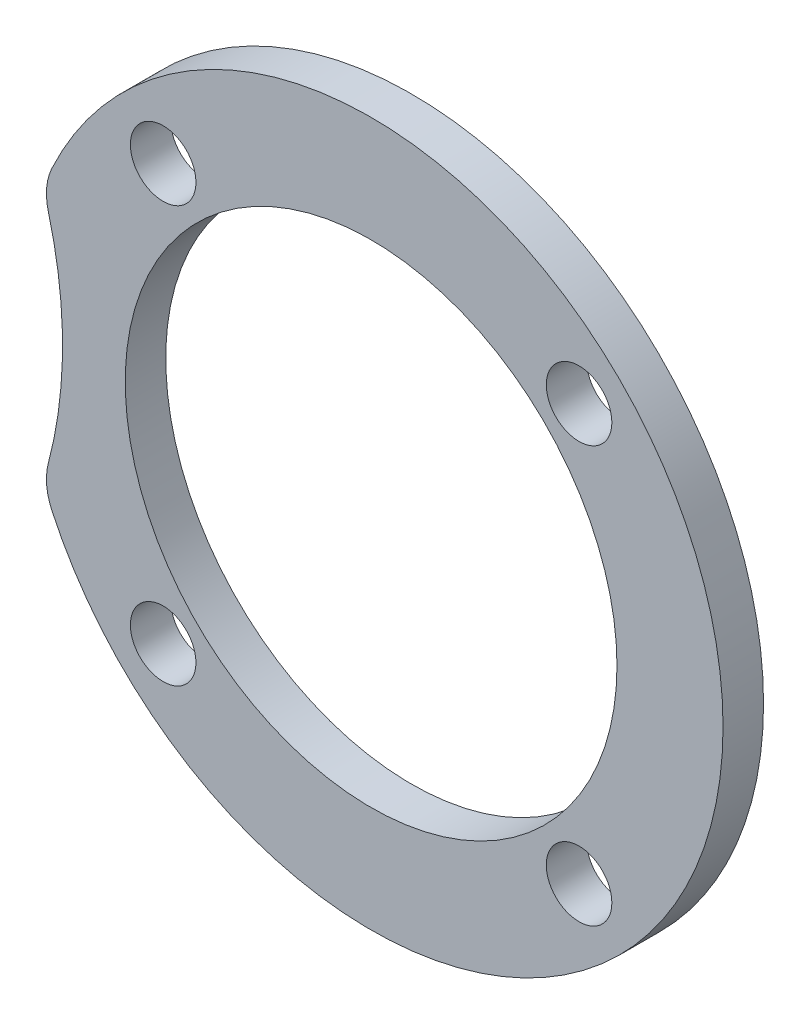
SolidWorks part; units mm, degrees
material "ABS"
ref_plane "前视基准面" through (0, 0, 0) normal (0, 0, 1) x (1, 0, 0)
ref_plane "上视基准面" through (0, 0, 0) normal (0, 1, 0) x (1, 0, 0)
ref_plane "右视基准面" through (0, 0, 0) normal (1, 0, 0) x (0, 0, -1)
sketch "草图1" plane through (0, 0, 0) normal (0, 0, 1) x (1, 0, 0)
  circle A0 centre (0, 0) radius 12.75
  circle A1 centre (0, 0) radius 18.25
  dimension "D1" = 25.5
  dimension "D2" = 36.5
extrude "凸台-拉伸1" add sketch "草图1" along normal mid plane 2.1
sketch "草图2" plane through (0, 0, 1.05) normal (0, 0, 1) x (1, 0, 0)
  line L0 (-38, 0) -> (0, 0) construction
  circle A0 centre (-38, 0) radius 22
  dimension "D1" = 44
  dimension "D2" = 38
extrude "切除-拉伸1" cut sketch "草图2" against normal mid plane 42.1
sketch "草图3" plane through (0, 0, 1.05) normal (0, 0, 1) x (1, 0, 0)
  line L0 (0, 15.25) -> (0, 0) construction
  line L1 (0, 0) -> (10.7834, 10.7834) construction
  circle A0 centre (0, 0) radius 15.25 construction
  arc A1 (-17.014, -6.602) -> (-17.014, 6.602) centre (0, 0) ccw construction
  circle A2 centre (10.7834, 10.7834) radius 1.7
  circle A3 centre (10.7834, -10.7834) radius 1.7
  circle A4 centre (-10.7834, -10.7834) radius 1.7
  circle A5 centre (-10.7834, 10.7834) radius 1.7
  point P18 (0, 0)
  dimension "D1" = 3
  dimension "D3" = 3.4
  dimension "D2" = 45
  dimension "D4" = 4
extrude "切除-拉伸2" cut sketch "草图3" against normal mid plane 32.1
fillet "圆角1" radius 3 2 edges at (-17.014, 6.602, 0) (-17.014, -6.602, 0)
